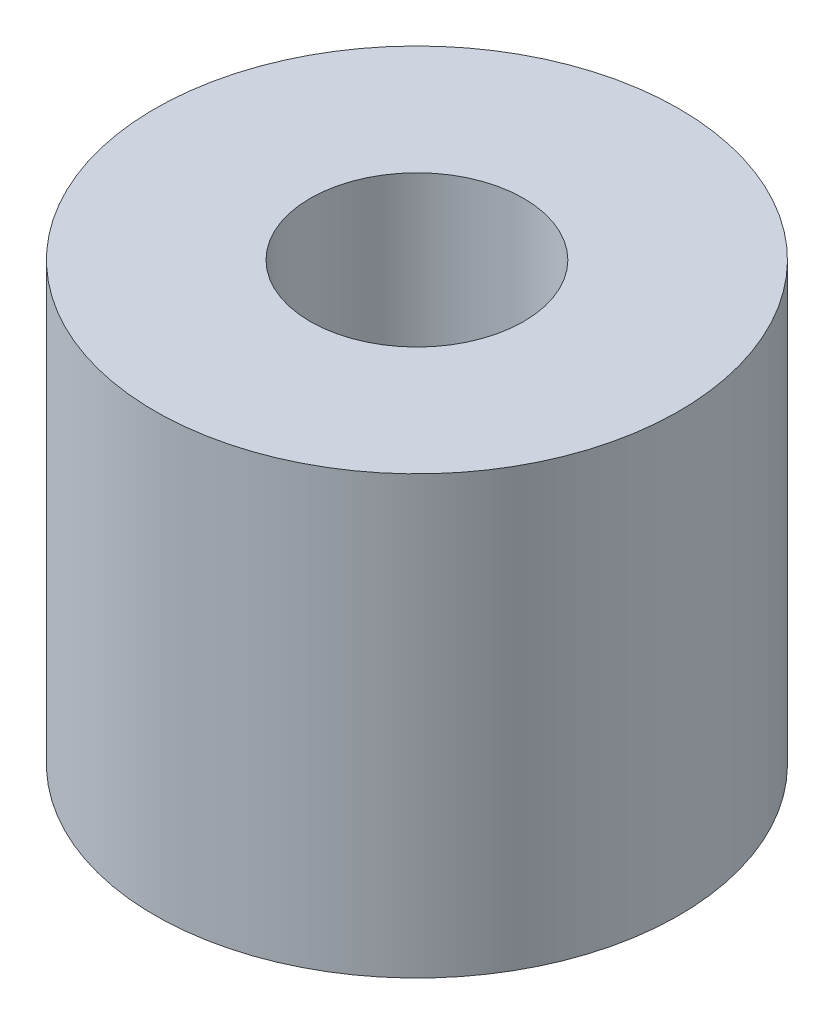
SolidWorks part; units mm, degrees
ref_plane "前视基准面" through (0, 0, 0) normal (0, 0, 1) x (1, 0, 0)
ref_plane "上视基准面" through (0, 0, 0) normal (0, 1, 0) x (1, 0, 0)
ref_plane "右视基准面" through (0, 0, 0) normal (1, 0, 0) x (0, 0, -1)
sketch "草图1" plane through (0, 0, 0) normal (0, 1, 0) x (1, 0, 0)
  circle A0 centre (0, 0) radius 27
extrude "凸台-拉伸1" add sketch "草图1" along normal blind 45
sketch "草图2" plane through (0, 45, 0) normal (0, 1, 0) x (1, 0, 0)
  circle A0 centre (0, 0) radius 11
extrude "切除-拉伸1" cut sketch "草图2" against normal blind 20
sketch "草图3" plane through (0, 0, 0) normal (0, -1, 0) x (1, 0, 0)
  line L0 (0, 10.4354) -> (0, -9.5509) construction
  line L2 (-10.4987, 0) -> (10.7865, 0) construction
  line L3 (-2.6, 10.2) -> (2.6, 10.2)
  line L4 (-2.6, 10.2) -> (-2.6, 6.4992)
  line L6 (2.6, 10.2) -> (2.6, 6.4992)
  arc A0 (-2.6, 6.4992) -> (2.6, 6.4992) centre (0, 0) ccw
  dimension "D1" = 5.2
  dimension "D2" = 10.2
extrude "切除-拉伸2" cut sketch "草图3" against normal blind 20 contours L3 L6 A0 L4
